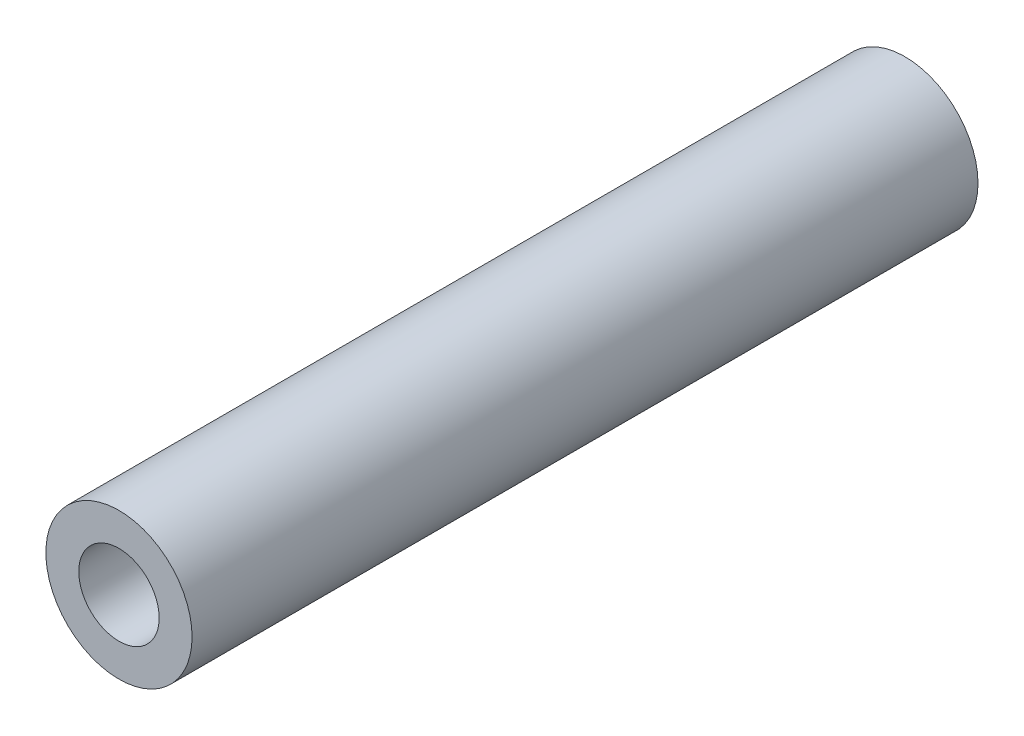
SolidWorks part; units mm, degrees
ref_plane "Front Plane" through (0, 0, 0) normal (0, 0, 1) x (1, 0, 0)
ref_plane "Top Plane" through (0, 0, 0) normal (0, 1, 0) x (1, 0, 0)
ref_plane "Right Plane" through (0, 0, 0) normal (1, 0, 0) x (0, 0, -1)
sketch "M4 clearance profile" plane through (0, 0, 0) normal (0, 0, 1) x (1, 0, 0)
  circle A0 centre (0, 0) radius 4
  circle A1 centre (0, 0) radius 2.2
extrude "M4 clearance" add sketch "M4 clearance profile" along normal blind 43
